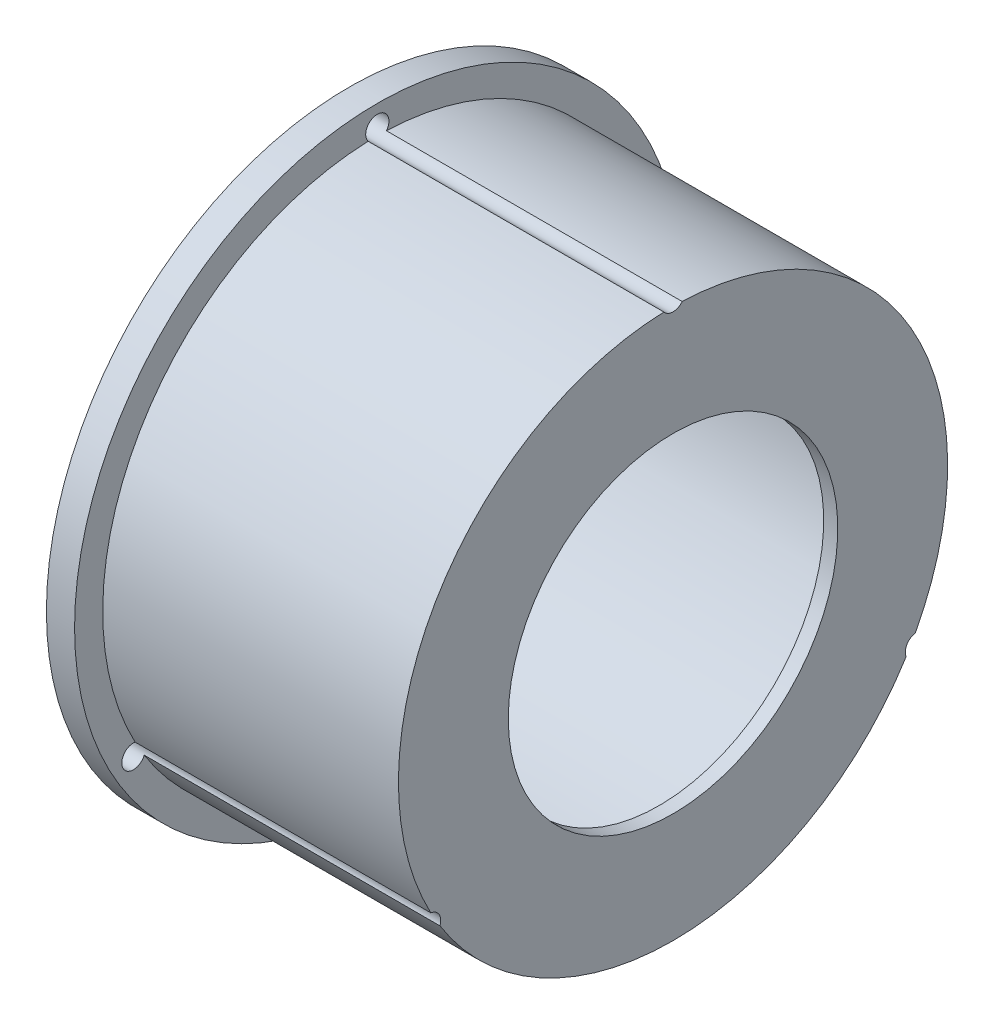
SolidWorks part; units mm, degrees
ref_plane "Front Plane" through (0, 0, 0) normal (0, 0, 1) x (1, 0, 0)
ref_plane "Top Plane" through (0, 0, 0) normal (0, 1, 0) x (1, 0, 0)
ref_plane "Right Plane" through (0, 0, 0) normal (1, 0, 0) x (0, 0, -1)
sketch "Axial profile (mm)" plane through (0, 0, 0) normal (0, 0, 1) x (1, 0, 0)
  line L0 (-110, 0) -> (75, 0) construction
  line L1 (135.7, 36.4) -> (179.7, 36.4)
  line L2 (179.7, 36.4) -> (179.7, 23.4)
  line L3 (179.7, 23.4) -> (181.7, 23.4)
  line L4 (181.7, 23.4) -> (181.7, 39)
  line L5 (181.7, 39) -> (139.7, 39)
  line L6 (139.7, 39) -> (139.7, 43)
  line L7 (139.7, 43) -> (135.7, 43)
  line L8 (135.7, 43) -> (135.7, 36.4)
revolve "Full revolution" add sketch "Axial profile (mm)" angle 360 about L0
sketch "Sketch2" plane through (0, 0, 0) normal (1, 0, 0) x (0, 0, -1)
  circle A0 centre (0, 40) radius 1.65
  circle A1 centre (-34.641, -20) radius 1.65
  circle A2 centre (34.641, -20) radius 1.65
extrude "Axial holes" cut sketch "Sketch2" along normal through all and the other way through all
